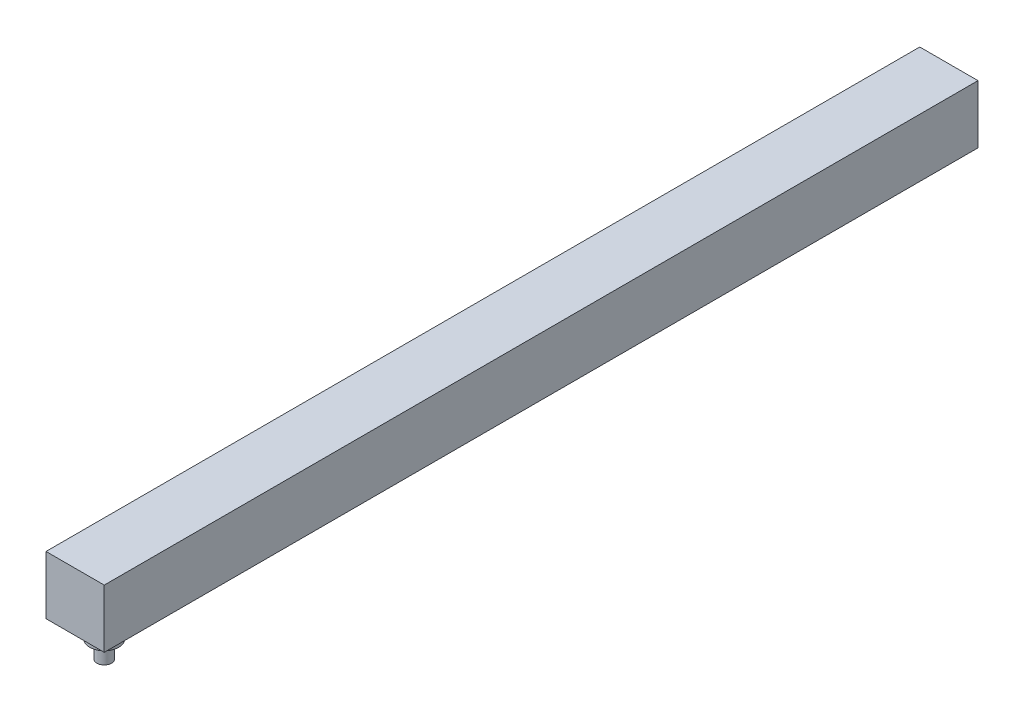
SolidWorks part; units mm, degrees
ref_plane "Front Plane" through (0, 0, 0) normal (0, 0, 1) x (1, 0, 0)
ref_plane "Top Plane" through (0, 0, 0) normal (0, 1, 0) x (1, 0, 0)
ref_plane "Right Plane" through (0, 0, 0) normal (1, 0, 0) x (0, 0, -1)
sketch "Sketch1" plane through (0, 0, 0) normal (0, 0, 1) x (1, 0, 0)
  line L1 (0, 0) -> (10, 0)
  line L2 (0, 0) -> (0, -10)
  line L3 (0, -10) -> (10, -10)
  line L4 (10, 0) -> (10, -10)
  dimension "D1" = 10
extrude "Boss-Extrude1" add sketch "Sketch1" along normal blind 150
sketch "Sketch2" plane through (0, -10, 0) normal (0, -1, 0) x (1, 0, 0)
  line L0 (0, 150) -> (10, 150) construction
  circle A0 centre (5, 145) radius 2.5
  point P4 (0, 0)
  point P5 (5, 150)
  dimension "D1" = 5
  dimension "D2" = 5
sketch "Sketch3" plane through (0, -10, 0) normal (0, -1, 0) x (1, 0, 0)
  circle A0 centre (5, 145) radius 1.25
  point P3 (5, 95)
  dimension "D1" = 2.5
extrude "Boss-Extrude2" add sketch "Sketch2" along normal blind 3 contours A0
extrude "Boss-Extrude3" add sketch "Sketch3" along normal blind 6
